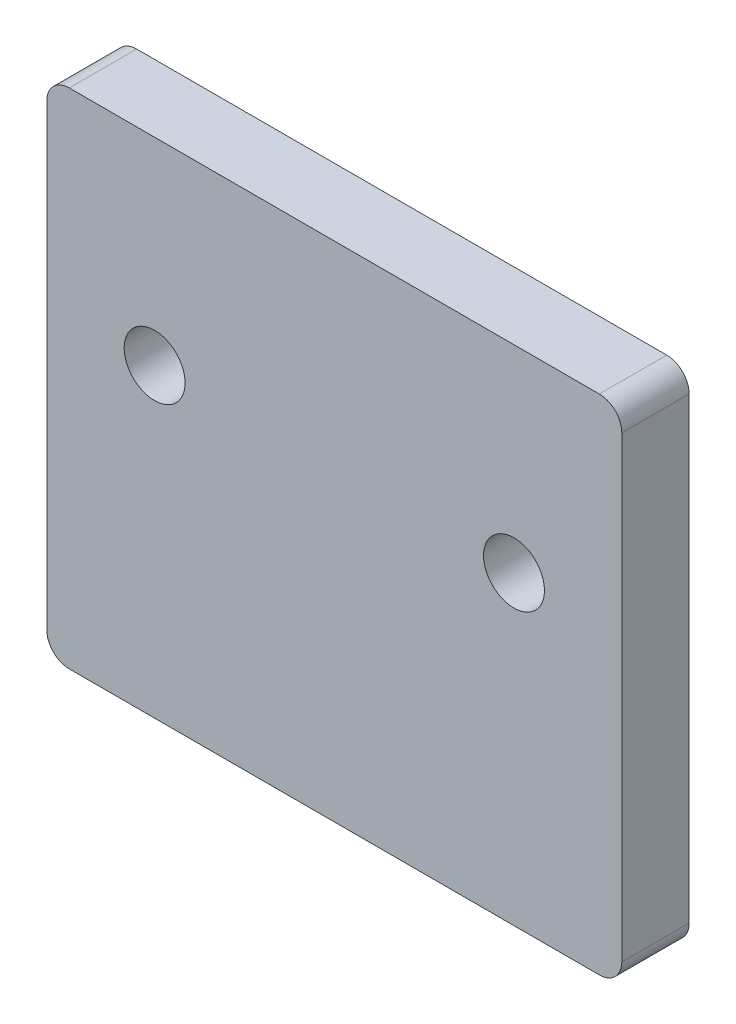
SolidWorks part; units mm, degrees
material "Acrylic (Medium-high impact)"
ref_plane "Front Plane" through (0, 0, 0) normal (0, 0, 1) x (1, 0, 0)
ref_plane "Top Plane" through (0, 0, 0) normal (0, 1, 0) x (1, 0, 0)
ref_plane "Right Plane" through (0, 0, 0) normal (1, 0, 0) x (0, 0, -1)
sketch "Sketch1" plane through (0, 0, 0) normal (0, 0, 1) x (1, 0, 0)
  line L4 (0, 1.5875) -> (0, 33.9725)
  line L5 (-1.5875, 35.56) -> (-39.0525, 35.56)
  line L6 (-40.64, 33.9725) -> (-40.64, 1.5875)
  line L7 (-39.0525, 0) -> (-1.5875, 0)
  line L8 (0, 1.5875) -> (0, 33.9725)
  line L9 (-1.5875, 35.56) -> (-39.0525, 35.56)
  line L10 (-40.64, 33.9725) -> (-40.64, 1.5875)
  line L11 (-39.0525, 0) -> (-1.5875, 0)
  circle A0 centre (-7.62, 21.59) radius 2.1526 construction
  circle A1 centre (-33.02, 21.59) radius 2.1526 construction
  circle A2 centre (-7.62, 21.59) radius 2.1526
  circle A3 centre (-33.02, 21.59) radius 2.1526
  arc A4 (-1.5875, 0) -> (0, 1.5875) centre (-1.5875, 1.5875) ccw
  arc A5 (0, 33.9725) -> (-1.5875, 35.56) centre (-1.5875, 33.9725) ccw
  arc A6 (-39.0525, 35.56) -> (-40.64, 33.9725) centre (-39.0525, 33.9725) ccw
  arc A7 (-40.64, 1.5875) -> (-39.0525, 0) centre (-39.0525, 1.5875) ccw
  arc A8 (-1.5875, 0) -> (0, 1.5875) centre (-1.5875, 1.5875) ccw
  arc A9 (0, 33.9725) -> (-1.5875, 35.56) centre (-1.5875, 33.9725) ccw
  arc A10 (-39.0525, 35.56) -> (-40.64, 33.9725) centre (-39.0525, 33.9725) ccw
  arc A11 (-40.64, 1.5875) -> (-39.0525, 0) centre (-39.0525, 1.5875) ccw
  dimension "D1" = 0
extrude "Boss-Extrude1" add sketch "Sketch1" along normal blind 4.7625
